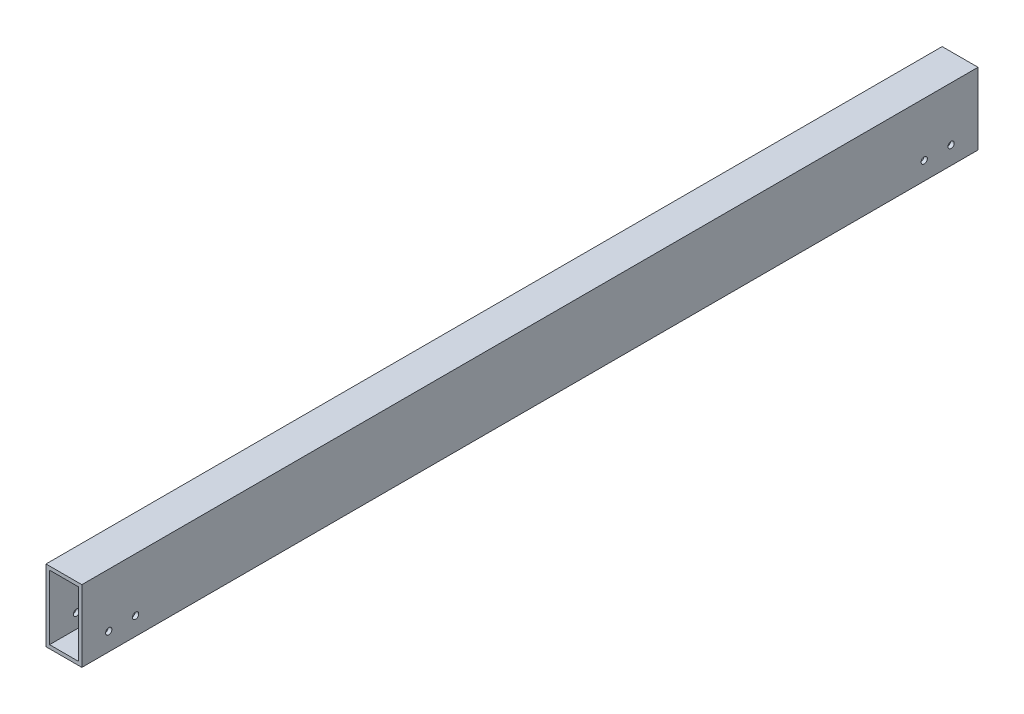
SolidWorks part; units mm, degrees
ref_plane "Plano frontal" through (0, 0, 0) normal (0, 0, 1) x (1, 0, 0)
ref_plane "Plano superior" through (0, 0, 0) normal (0, 1, 0) x (1, 0, 0)
ref_plane "Plano direito" through (0, 0, 0) normal (1, 0, 0) x (0, 0, -1)
sketch "Esboço1" plane through (0, 0, 0) normal (0, 0, 1) x (1, 0, 0)
  line L2 (0, 0) -> (20, 0)
  line L3 (0, 0) -> (0, 40)
  line L4 (0, 40) -> (20, 40)
  line L5 (20, 0) -> (20, 40)
  line L7 (2, 2) -> (18, 2)
  line L8 (2, 2) -> (2, 38)
  line L9 (2, 38) -> (18, 38)
  line L10 (18, 2) -> (18, 38)
  dimension "D1" = 40
  dimension "D2" = 20
  dimension "D3" = 2
  dimension "D4" = 2
  dimension "D5" = 2
  dimension "D6" = 2
extrude "Ressalto-extrusão1" add sketch "Esboço1" along normal blind 500
sketch "Esboço2" plane through (0, 0, 0) normal (-1, 0, 0) x (0, 0, 1)
  line L0 (0, 40) -> (0, 0) construction
  line L1 (500, 0) -> (0, 0) construction
  line L2 (250, 40) -> (250, 0) construction
  line L3 (500, 40) -> (0, 40) construction
  circle A2 centre (15, 10) radius 1.75
  circle A3 centre (30, 10) radius 1.75
  circle A4 centre (485, 10) radius 1.75
  circle A5 centre (470, 10) radius 1.75
  dimension "D1" = 15
  dimension "D2" = 10
  dimension "D7" = 3.5
  dimension "D8" = 3.5
  dimension "D9" = 15
extrude "Corte-extrusão1" cut sketch "Esboço2" against normal blind 2
sketch "Esboço5" plane through (20, 0, 0) normal (1, 0, 0) x (0, 0, -1)
  line L2 (-250, 40) -> (-250, 0) construction
  line L4 (0, 0) -> (0, 40) construction
  line L5 (-500, 40) -> (0, 40) construction
  line L6 (-500, 0) -> (0, 0) construction
  circle A4 centre (-15, 10) radius 1.75
  circle A5 centre (-30, 10) radius 1.75
  circle A6 centre (-485, 10) radius 1.75
  circle A7 centre (-470, 10) radius 1.75
  dimension "D1" = 10
  dimension "D2" = 15
  dimension "D3" = 10
extrude "Corte-extrusão2" cut sketch "Esboço5" against normal blind 2
